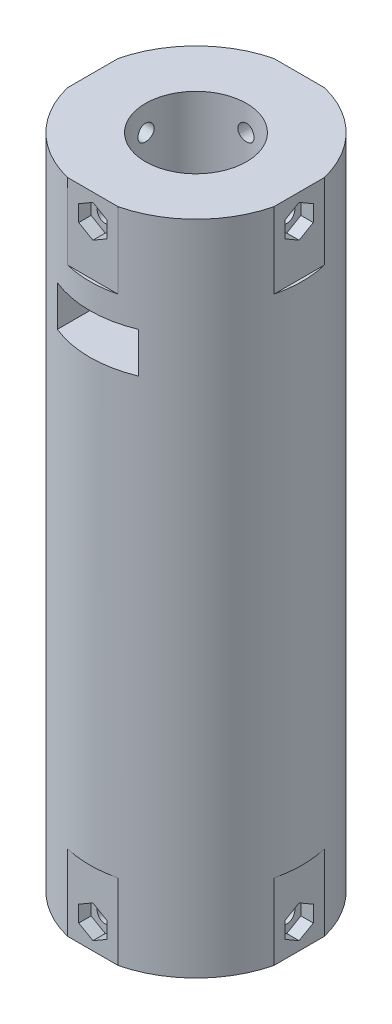
SolidWorks part; units mm, degrees
ref_plane "前视基准面" through (0, 0, 0) normal (0, 0, 1) x (1, 0, 0)
ref_plane "上视基准面" through (0, 0, 0) normal (0, 1, 0) x (1, 0, 0)
ref_plane "右视基准面" through (0, 0, 0) normal (1, 0, 0) x (0, 0, -1)
sketch "草图1" plane through (0, 0, 0) normal (0, 1, 0) x (1, 0, 0)
  circle A0 centre (0, 0) radius 21
  circle A1 centre (0, 0) radius 10
extrude "凸台-拉伸1" add sketch "草图1" along normal blind 45
ref_plane "基准面5" through (0, 45, 0) normal (0, 1, 0) x (1, 0, 0)
sketch "草图4" plane through (0, 45, 0) normal (0, 1, 0) x (1, 0, 0)
  circle A0 centre (0, 0) radius 21
  circle A1 centre (0, 0) radius 10
extrude "凸台-拉伸2" add sketch "草图4" along normal blind 85
ref_plane "基准面6" through (0, 130, 0) normal (0, 1, 0) x (1, 0, 0)
sketch "草图11" plane through (0, 0, 0) normal (0, 1, 0) x (1, 0, 0)
  line L1 (5, -5) -> (-5, -5) construction
  line L2 (5, -5) -> (5, 5) construction
  line L3 (5, 5) -> (-5, 5) construction
  line L4 (-5, -5) -> (-5, 5) construction
  line L5 (5, -5) -> (-5, 5) construction
  line L6 (5, 5) -> (-5, -5) construction
  line L7 (-20.3961, 5) -> (-20.3961, -5)
  line L10 (-5, -20.3961) -> (5, -20.3961)
  line L13 (20.3961, -5) -> (20.3961, 5)
  line L16 (5, 20.3961) -> (-5, 20.3961)
  arc A0 (5, 20.3961) -> (-5, 20.3961) centre (0, 0) ccw
  arc A1 (-20.3961, 5) -> (-20.3961, -5) centre (0, 0) ccw
  arc A2 (-5, -20.3961) -> (5, -20.3961) centre (0, 0) ccw
  arc A3 (20.3961, -5) -> (20.3961, 5) centre (0, 0) ccw
  dimension "D1" = 10
  dimension "D2" = 10
extrude "切除-拉伸3" cut sketch "草图11" along normal blind 15
sketch "草图5" plane through (0, 130, 0) normal (0, 1, 0) x (1, 0, 0)
  line L1 (-5, -5) -> (5, -5) construction
  line L2 (-5, -5) -> (-5, 5) construction
  line L3 (-5, 5) -> (5, 5) construction
  line L4 (5, -5) -> (5, 5) construction
  line L5 (-5, -5) -> (5, 5) construction
  line L6 (-5, 5) -> (5, -5) construction
  line L7 (-20.3961, 5) -> (-20.3961, -5)
  line L10 (-5, -20.3961) -> (5, -20.3961)
  line L13 (20.3961, -5) -> (20.3961, 5)
  line L16 (5, 20.3961) -> (-5, 20.3961)
  arc A2 (-20.3961, 5) -> (-20.3961, -5) centre (0, 0) ccw
  arc A3 (-5, -20.3961) -> (5, -20.3961) centre (0, 0) ccw
  arc A4 (20.3961, -5) -> (20.3961, 5) centre (0, 0) ccw
  arc A5 (5, 20.3961) -> (-5, 20.3961) centre (0, 0) ccw
  dimension "D1" = 10
  dimension "D2" = 10
extrude "切除-拉伸4" cut sketch "草图5" against normal blind 15
sketch "草图12" plane through (0, 0, 0) normal (0, 0, 1) x (1, 0, 0)
  line L0 (0, 130) -> (0, 115) construction
  line L3 (5, 130) -> (-5, 130) construction
  line L4 (0, 110) -> (8, 110)
  line L5 (8, 110) -> (8, 102)
  line L6 (8, 102) -> (-8, 102)
  line L7 (-8, 102) -> (-8, 110)
  line L8 (-8, 110) -> (0, 110)
  line L9 (5, 115) -> (-5, 115) construction
  line L10 (0, 115) -> (0, 110) construction
  dimension "D1" = 8
  dimension "D2" = 16
  dimension "D3" = 8
extrude "切除-拉伸6" cut sketch "草图12" along normal blind 25
sketch "草图13" plane through (0, 0, 0) normal (1, 0, 0) x (0, 0, -1)
  line L2 (0, 128.2332) -> (-2.8, 126.6166)
  line L3 (5, 115) -> (5, 130) construction
  line L4 (5, 120) -> (-5, 130) construction
  line L5 (-2.8, 126.6166) -> (-2.8, 123.3834)
  line L6 (-2.8, 123.3834) -> (0, 121.7668)
  line L7 (0, 121.7668) -> (2.8, 123.3834)
  line L8 (2.8, 123.3834) -> (2.8, 126.6166)
  line L9 (2.8, 126.6166) -> (0, 128.2332)
  line L10 (5, 15) -> (5, 0) construction
  line L11 (5, 10) -> (-5, 0) construction
  line L12 (0, 8.2332) -> (-2.8, 6.6166)
  line L13 (-2.8, 6.6166) -> (-2.8, 3.3834)
  line L14 (-2.8, 3.3834) -> (0, 1.7668)
  line L15 (0, 1.7668) -> (2.8, 3.3834)
  line L16 (2.8, 3.3834) -> (2.8, 6.6166)
  line L17 (2.8, 6.6166) -> (0, 8.2332)
  circle A0 centre (0, 125) radius 2.8 construction
  circle A1 centre (0, 5) radius 2.8 construction
extrude "切除-拉伸7" cut sketch "草图13" against normal blind 2.45 from offset 20.4
pattern_circular "阵列(圆周)1" count 4 every 90 about axis through (0, 0, 0) along (0, 1, 0) of "切除-拉伸7"
sketch "草图14" plane through (0, 0, 0) normal (1, 0, 0) x (0, 0, -1)
  line L0 (0, 128.2332) -> (0, 121.7668) construction
  line L1 (0, 8.2332) -> (0, 1.7668) construction
  circle A0 centre (0, 125) radius 1.6
  circle A1 centre (0, 5) radius 1.6
extrude "切除-拉伸8" cut sketch "草图14" along normal blind 22.45
pattern_circular "阵列(圆周)2" count 4 every 90 about axis through (0, 45, 0) along (0, -1, 0) of "切除-拉伸8"
